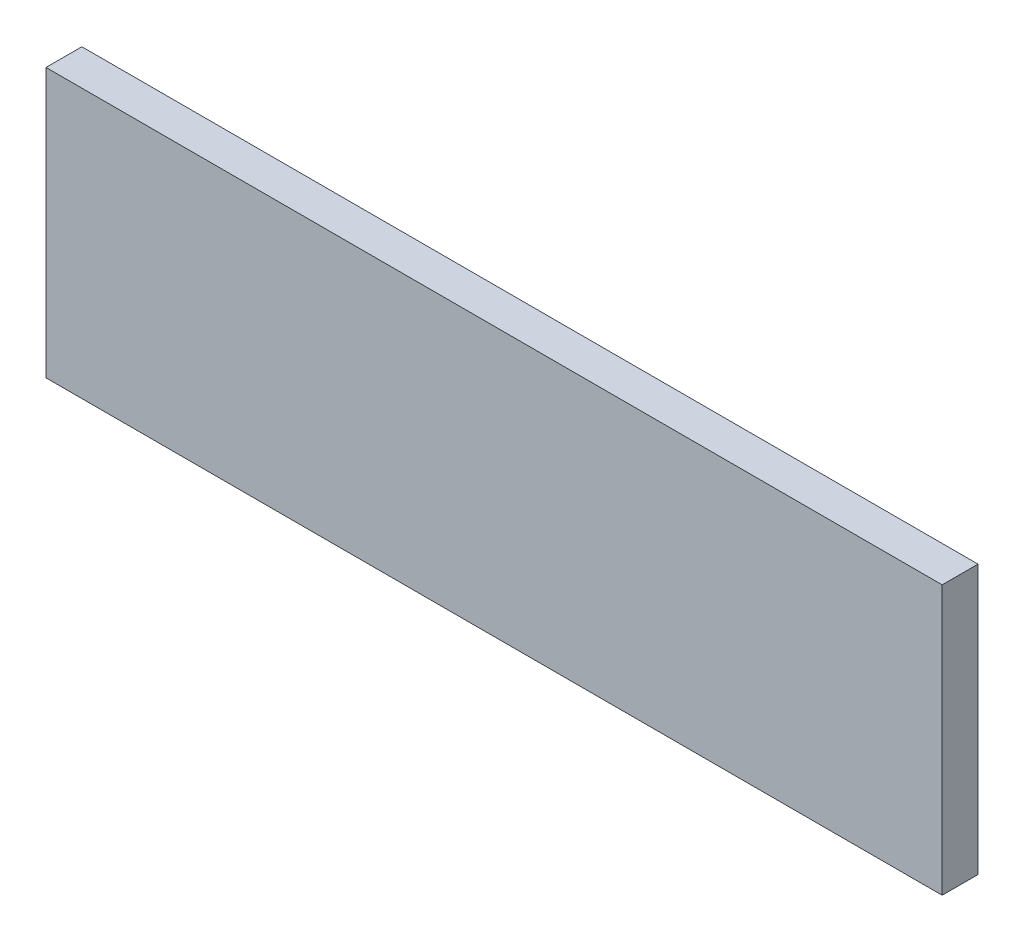
SolidWorks part; units mm, degrees
ref_plane "Plan de face" through (0, 0, 0) normal (0, 0, 1) x (1, 0, 0)
ref_plane "Plan de dessus" through (0, 0, 0) normal (0, 1, 0) x (1, 0, 0)
ref_plane "Plan de droite" through (0, 0, 0) normal (1, 0, 0) x (0, 0, -1)
sketch "Esquisse1" plane through (0, 0, 0) normal (0, 0, 1) x (1, 0, 0)
  line L1 (-64.5455, 11.4336) -> (35.4545, 11.4336)
  line L2 (-64.5455, 11.4336) -> (-64.5455, -18.5664)
  line L3 (-64.5455, -18.5664) -> (35.4545, -18.5664)
  line L4 (35.4545, 11.4336) -> (35.4545, -18.5664)
  dimension "D1" = 30
  dimension "D2" = 100
extrude "Boss.-Extru.1" add sketch "Esquisse1" along normal blind 4
